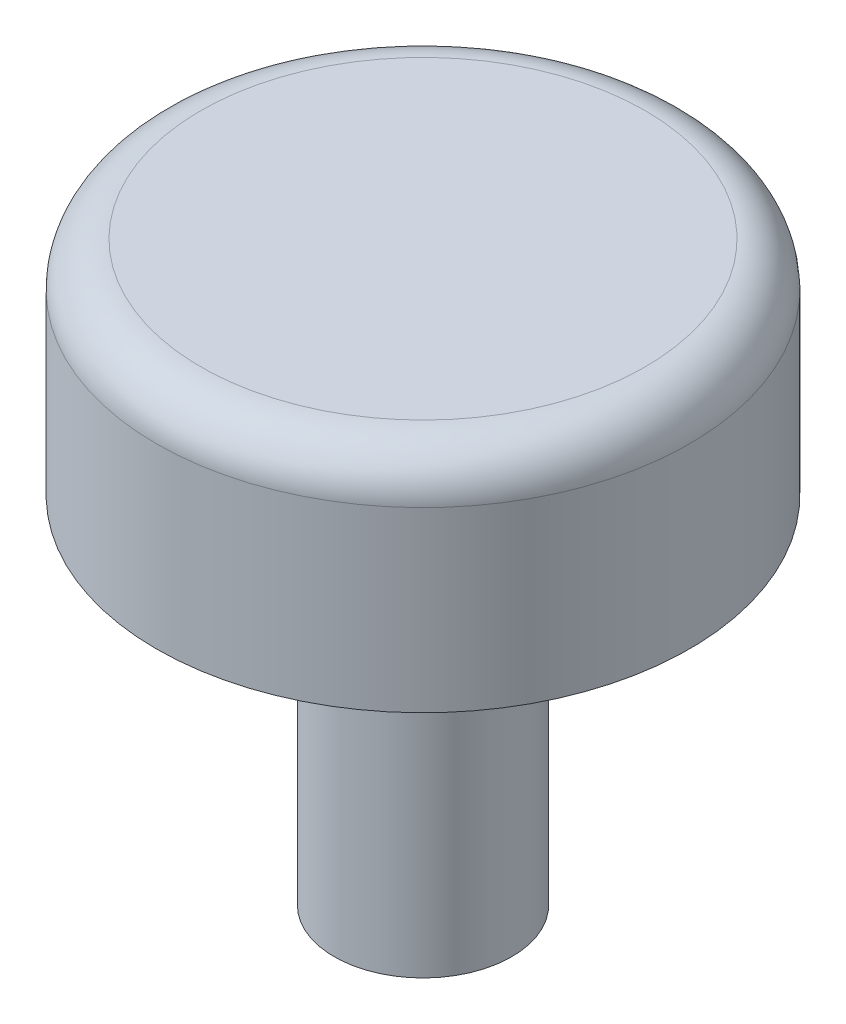
SolidWorks part; units mm, degrees
ref_plane "Front Plane" through (0, 0, 0) normal (0, 0, 1) x (1, 0, 0)
ref_plane "Top Plane" through (0, 0, 0) normal (0, 1, 0) x (1, 0, 0)
ref_plane "Right Plane" through (0, 0, 0) normal (1, 0, 0) x (0, 0, -1)
sketch "Sketch1" plane through (0, 0, 0) normal (1, 0, 0) x (0, 0, -1)
  line L0 (0, 0) -> (0, 13)
  line L1 (0, 13) -> (5, 13)
  line L2 (6, 12) -> (6, 8)
  line L3 (6, 8) -> (2, 8)
  line L4 (2, 8) -> (2, 0)
  line L5 (2, 0) -> (0, 0)
  arc A0 (6, 12) -> (5, 13) centre (5, 12) ccw
  point P10 (6, 13)
  dimension "D5" = 1
  dimension "D1" = 2
  dimension "D2" = 5
  dimension "D3" = 6
  dimension "D4" = 8
revolve "Revolve1" add sketch "Sketch1" angle 360 about L0
